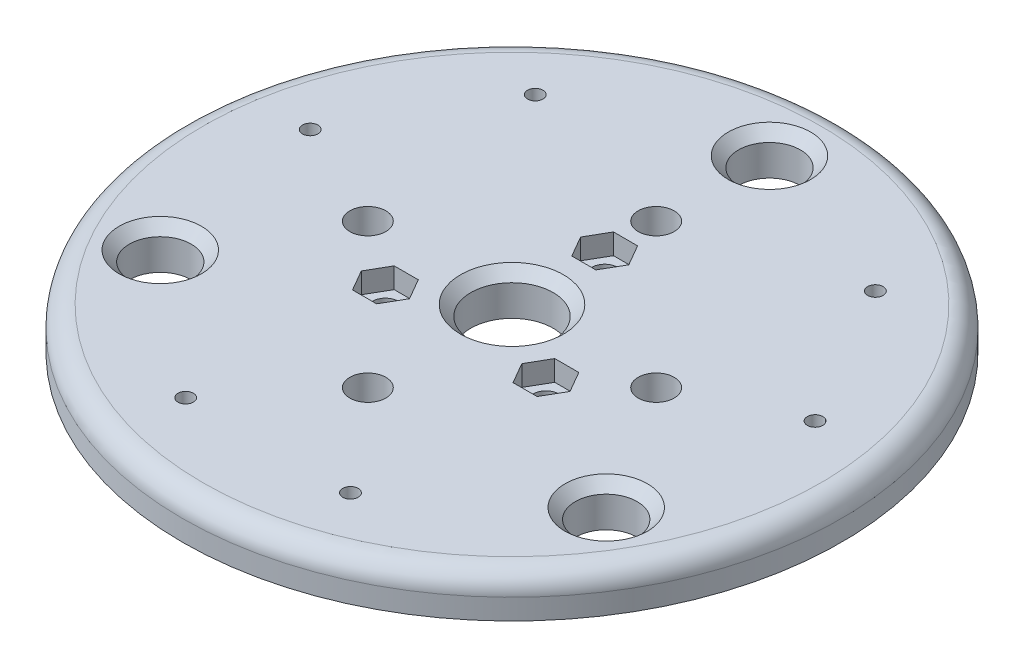
SolidWorks part; units mm, degrees
ref_plane "Спереди" through (0, 0, 0) normal (0, 0, 1) x (1, 0, 0)
ref_plane "Сверху" through (0, 0, 0) normal (0, 1, 0) x (1, 0, 0)
ref_plane "Справа" through (0, 0, 0) normal (1, 0, 0) x (0, 0, -1)
sketch "Эскиз1" plane through (0, 0, 0) normal (0, 1, 0) x (1, 0, 0)
  circle A3 centre (0, 0) radius 32
  circle A4 centre (0, 0) radius 4
  circle A6 centre (0, 0) radius 25 construction
  circle A7 centre (0, 25) radius 3
  circle A8 centre (21.6506, -12.5) radius 3
  circle A9 centre (-21.6506, -12.5) radius 3
  dimension "D4" = 64
  dimension "D1" = 8
  dimension "D2" = 50
  dimension "D3" = 6
  dimension "D5" = 3
extrude "Бобышка-Вытянуть1" add sketch "Эскиз1" along normal blind 4
fillet "Скругление1" radius 2 1 edges at (0, 4, 32)
sketch "Эскиз2" plane through (0, 4, 0) normal (0, 1, 0) x (1, 0, 0)
  circle A0 centre (0, 0) radius 9 construction
  circle A1 centre (0, 9) radius 1.25
  circle A2 centre (7.7942, -4.5) radius 1.25
  circle A3 centre (-7.7942, -4.5) radius 1.25
  dimension "D1" = 18
  dimension "D2" = 2.5
  dimension "D3" = 3
extrude "Вырез-Вытянуть1" cut sketch "Эскиз2" against normal through all
sketch "Эскиз3" plane through (0, 0, 0) normal (0, -1, 0) x (1, 0, 0)
  circle A0 centre (0, 0) radius 14 construction
  circle A1 centre (0, 14) radius 1.75
  circle A2 centre (14, 0) radius 1.75
  circle A3 centre (0, -14) radius 1.75
  circle A4 centre (-14, 0) radius 1.75
  dimension "D1" = 28
  dimension "D2" = 3.5
  dimension "D3" = 4
extrude "Вырез-Вытянуть2" cut sketch "Эскиз3" against normal through all
sketch "Эскиз4" plane through (0, 4, 0) normal (0, 1, 0) x (1, 0, 0)
  line L0 (5.456, -4.5) -> (6.6251, -6.525)
  line L1 (1.1691, 6.975) -> (2.3383, 9)
  line L2 (2.3383, 9) -> (1.1691, 11.025)
  line L3 (1.1691, 11.025) -> (-1.1691, 11.025)
  line L4 (-1.1691, 11.025) -> (-2.3383, 9)
  line L5 (-2.3383, 9) -> (-1.1691, 6.975)
  line L6 (-1.1691, 6.975) -> (1.1691, 6.975)
  line L7 (6.6251, -6.525) -> (8.9634, -6.525)
  line L8 (8.9634, -6.525) -> (10.1325, -4.5)
  line L9 (10.1325, -4.5) -> (8.9634, -2.475)
  line L10 (8.9634, -2.475) -> (6.6251, -2.475)
  line L11 (6.6251, -2.475) -> (5.456, -4.5)
  line L12 (-6.6251, -2.475) -> (-8.9634, -2.475)
  line L13 (-8.9634, -2.475) -> (-10.1325, -4.5)
  line L14 (-10.1325, -4.5) -> (-8.9634, -6.525)
  line L15 (-8.9634, -6.525) -> (-6.6251, -6.525)
  line L16 (-6.6251, -6.525) -> (-5.456, -4.5)
  line L17 (-5.456, -4.5) -> (-6.6251, -2.475)
  circle A0 centre (0, 9) radius 2.025 construction
  circle A1 centre (7.7942, -4.5) radius 2.025 construction
  circle A2 centre (-7.7942, -4.5) radius 2.025 construction
  circle A3 centre (7.7942, -4.5) radius 1.25 construction
  dimension "D1" = 4.05
  dimension "D2" = 3
extrude "Вырез-Вытянуть3" cut sketch "Эскиз4" against normal blind 2
chamfer "Фаска1" distance 1 angle 45 4 edges at (0, 4, -22) (21.6506, 4, 15.5) (-21.6506, 4, 15.5) (0, 4, 4)
sketch "Эскиз5" plane through (0, 4, 0) normal (0, 1, 0) x (1, 0, 0)
  line L0 (0, 0) -> (0, -25) construction
  line L1 (8, -23.6854) -> (-8, -23.6854) construction
  circle A0 centre (0, 0) radius 25 construction
  circle A1 centre (-8, -23.6854) radius 0.75
  circle A2 centre (8, -23.6854) radius 0.75
  circle A3 centre (-16.5122, 18.7709) radius 0.75
  circle A4 centre (-24.5122, 4.9145) radius 0.75
  circle A5 centre (24.5122, 4.9145) radius 0.75
  circle A6 centre (16.5122, 18.7709) radius 0.75
  dimension "D2" = 1.5
  dimension "D3" = 1.5
  dimension "D1" = 16
  dimension "D4" = 3
extrude "Вырез-Вытянуть4" cut sketch "Эскиз5" against normal through all
equation "\"motor_diameter\"= 30"
equation "\"mm_diameter\"= IIF ( \"motor_diameter\" < 34 , 41 , \"motor_diameter\" + 8 )"
equation "\"upper_shafts_diameter\"= 5"
equation "\"upper_shats_length\"= 180"
equation "\"upper_bearing_d1\"= 10"
equation "\"upper_bearing_d2\"= 5"
equation "\"upper_bearing_h\"= 15"
equation "\"lower_shafts_diameter\"= 5"
equation "\"lower_shafts_length\"= 180"
equation "\"lower_bearing_d1\"= 10"
equation "\"lower_bearing_d2\"= 5"
equation "\"lower_bearing_h\"= 15"
equation "\"print_offset\"= 0.5"
equation "\"bh_screws_d\"= 2"
equation "\"bh_screws_h\"= 20"
equation "\"bh_screws_hh_d\"= 3.4"
equation "\"bh_screws_hh_h\"= 2"
equation "\"bh_nut_d\"= 3.8"
equation "\"bh_nut_h\"= 2"
equation "\"motor_screws_d\"= 3"
equation "\"motor_screws_h\"= 16"
equation "\"motor_screws_hh_d\"= 5.5"
equation "\"motor_screws_hh_h\"= 3"
equation "\"plate_hole_distance\"= 25.4"
equation "\"plate_screws_d\"= 6.5"
equation "\"shafts_diameter\"= IIF ( \"mm_diameter\" < 42 , 42 + 8 , \"mm_diameter\" + 8 )"
equation "\"D4@Эскиз1\"= \"system_radius\" * 2"
equation "\"central_hole_diameter\"= 8"
equation "\"bh_thikness\"= 4"
equation "\"D1@Эскиз1\"=\"central_hole_diameter\""
equation "\"D2@Эскиз1\"=\"shafts_diameter\""
equation "\"D3@Эскиз1\"=\"upper_shafts_diameter\"+1"
equation "\"D1@Бобышка-Вытянуть1\"=\"bh_thikness\""
equation "\"D2@Эскиз2\"=\"bh_screws_d\"+\"print_offset\""
equation "\"D2@Эскиз3\"=\"motor_screws_d\"+\"print_offset\""
equation "\"D1@Эскиз4\"=\"bh_nut_d\"+\"print_offset\"/2"
equation "\"D1@Вырез-Вытянуть3\"=\"bh_nut_h\""
equation "\"D2@Эскиз5\"=\"bh_screws_d\"-\"print_offset\""
equation "\"D3@Эскиз5\"=\"D2@Эскиз5\""
equation "\"ends_screws_d\"= 4"
equation "\"ends_screws_h\"= 16"
equation "\"ends_screws_hh_d\"= 6.7"
equation "\"ends_screws_hh_h\"= 4.1"
equation "\"ends_nut_d\"= 6.8"
equation "\"ends_nut_h\"= 3"
equation "\"system_radius\" = ( \"shafts_diameter\" + 12 + \"bh_thikness\" / 2 ) / 2"
equation "\"encoder_distance\"= \"system_radius\" + 4"
equation "\"tape_position\"= \"encoder_distance\" - 2 + 3.9 + 1.7 / 2"
